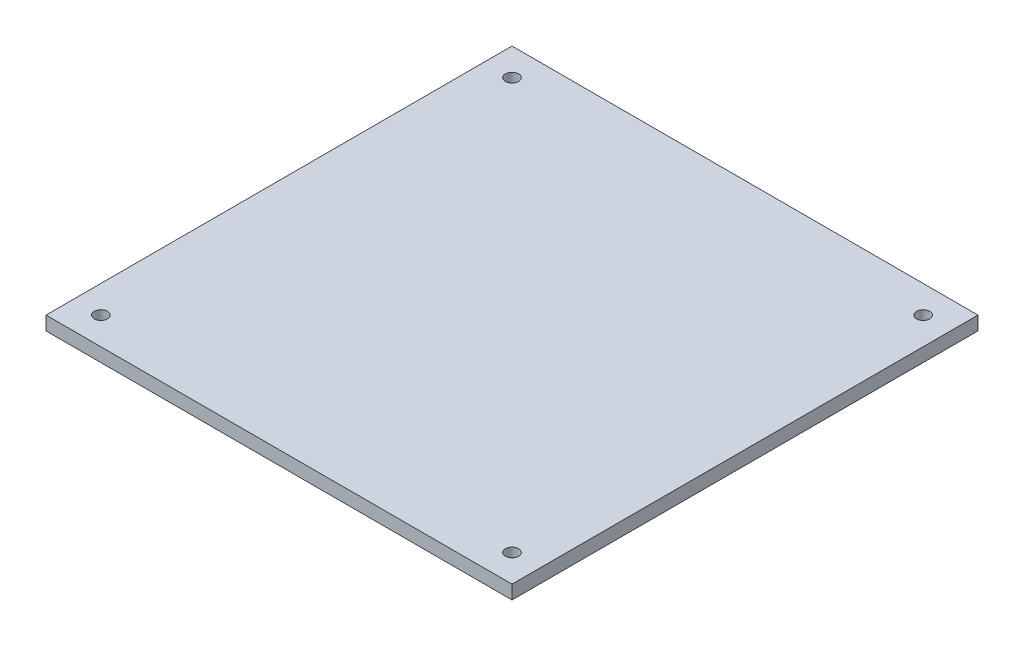
SolidWorks part; units mm, degrees
ref_plane "Front Plane" through (0, 0, 0) normal (0, 0, 1) x (1, 0, 0)
ref_plane "Top Plane" through (0, 0, 0) normal (0, 1, 0) x (1, 0, 0)
ref_plane "Right Plane" through (0, 0, 0) normal (1, 0, 0) x (0, 0, -1)
sketch "Sketch1" plane through (0, 0, 0) normal (0, 1, 0) x (1, 0, 0)
  line L1 (-42.5, 42.5) -> (42.5, 42.5)
  line L2 (-42.5, 42.5) -> (-42.5, -42.5)
  line L3 (-42.5, -42.5) -> (42.5, -42.5)
  line L4 (42.5, 42.5) -> (42.5, -42.5)
  line L5 (-42.5, 42.5) -> (42.5, -42.5) construction
  line L6 (-42.5, -42.5) -> (42.5, 42.5) construction
  point P0 (0, 0)
  dimension "D1" = 85
  dimension "D2" = 85
extrude "Boss-Extrude1" add sketch "Sketch1" along normal blind 2.5
sketch "Sketch2" plane through (0, 2.5, 0) normal (0, 1, 0) x (1, 0, 0)
  line L0 (-42.5, 42.5) -> (-42.5, -42.5) construction
  line L1 (42.5, 42.5) -> (-42.5, 42.5) construction
  line L2 (42.5, -42.5) -> (42.5, 42.5) construction
  line L3 (-42.5, -42.5) -> (42.5, -42.5) construction
  circle A0 centre (-37.5, 37.5) radius 1.2
  circle A2 centre (37.5, 37.5) radius 1.2
  circle A3 centre (37.5, -37.5) radius 1.2
  circle A4 centre (-37.5, -37.5) radius 1.2
  point P0 (-37.5, 37.5)
  point P3 (37.5, 37.5)
  point P8 (-37.5, -37.5)
  point P11 (37.5, -37.5)
  dimension "D1" = 5
  dimension "D2" = 5
  dimension "D3" = 5
  dimension "D4" = 5
  dimension "D5" = 5
  dimension "D6" = 5
  dimension "D7" = 5
  dimension "D8" = 5
extrude "Cut-Extrude3" cut sketch "Sketch2" against normal through all
